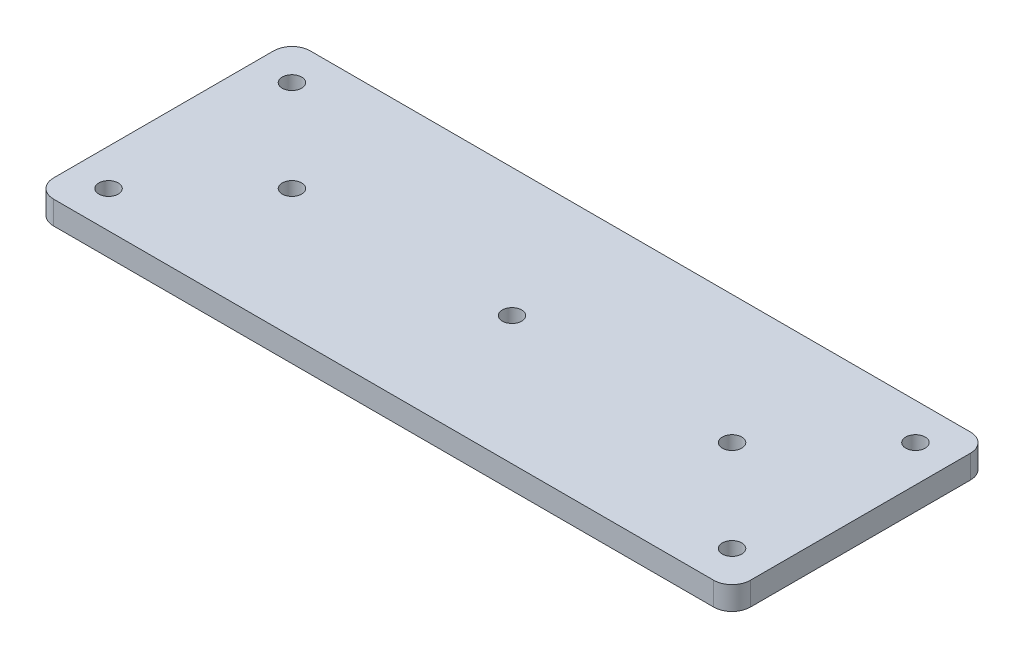
SolidWorks part; units mm, degrees
material "5052-H32"
ref_plane "Front Plane" through (0, 0, 0) normal (0, 0, 1) x (1, 0, 0)
ref_plane "Top Plane" through (0, 0, 0) normal (0, 1, 0) x (1, 0, 0)
ref_plane "Right Plane" through (0, 0, 0) normal (1, 0, 0) x (0, 0, -1)
sketch "Sketch1" plane through (0, 0, 0) normal (0, 1, 0) x (1, 0, 0)
  line L0 (-60, 0) -> (60, 0) construction
  line L1 (-85, 25) -> (85, 25) construction
  line L2 (-85, 25) -> (-85, -25) construction
  line L3 (-85, -25) -> (85, -25) construction
  line L4 (85, 25) -> (85, -25) construction
  line L5 (-95, 35) -> (95, 35)
  line L6 (-95, 35) -> (-95, -35)
  line L7 (-95, -35) -> (95, -35)
  line L8 (95, 35) -> (95, -35)
  circle A0 centre (-85, 25) radius 2.5 construction
  circle A1 centre (85, 25) radius 2.5 construction
  circle A2 centre (85, -25) radius 2.5 construction
  circle A3 centre (-85, -25) radius 2.5 construction
  circle A4 centre (-60, 0) radius 2.5 construction
  circle A5 centre (60, 0) radius 2.5 construction
  circle A6 centre (0, 0) radius 2.5 construction
  point P8 (0, 25)
  point P10 (-85, 0)
  point P15 (0, 35)
  point P16 (-95, 0)
  point P21 (0, 0)
  dimension "D1" = 5
  dimension "D6" = 5
  dimension "D2" = 170
  dimension "D3" = 50
  dimension "D4" = 190
  dimension "D5" = 70
  dimension "D7" = 120
extrude "Boss-Extrude1" add sketch "Sketch1" against normal blind 6.35 contours L5 L8 L7 L6
hole_wizard "M5 Clearance Hole1" positions "3DSketch2" profile "Sketch3" hole size "M5" standard "ANSI Metric" end condition up to next
sketch3d "3DSketch2"
  point P0 (-85, 0, -25)
  point P2 (-85, 0, 25)
  point P4 (60, 0, 0)
  point P6 (85, 0, -25)
  point P8 (0, 0, 0)
  point P10 (-60, 0, 0)
  point P25 (85, 0, 25)
  point P28 (85, 0, 25)
sketch "Sketch3" plane through (-85, 0, -25) normal (1, 0, 0) x (0, 0, 1)
  line L0 (0, 0) -> (0, 6.35)
  line L1 (0, 6.35) -> (2.65, 6.35)
  line L2 (2.65, 6.35) -> (2.65, 0)
  line L5 (2.65, 0) -> (0, 0)
  line L11 (0, -6.35) -> (0, 107.95) construction
  dimension "Thru Hole Dia." = 5.3
  dimension "Thru Hole Depth" = 6.35
fillet "Fillet1" radius 5 4 edges at (-95, -3.175, -35) (-95, -3.175, 35) (95, -3.175, -35) (95, -3.175, 35)
